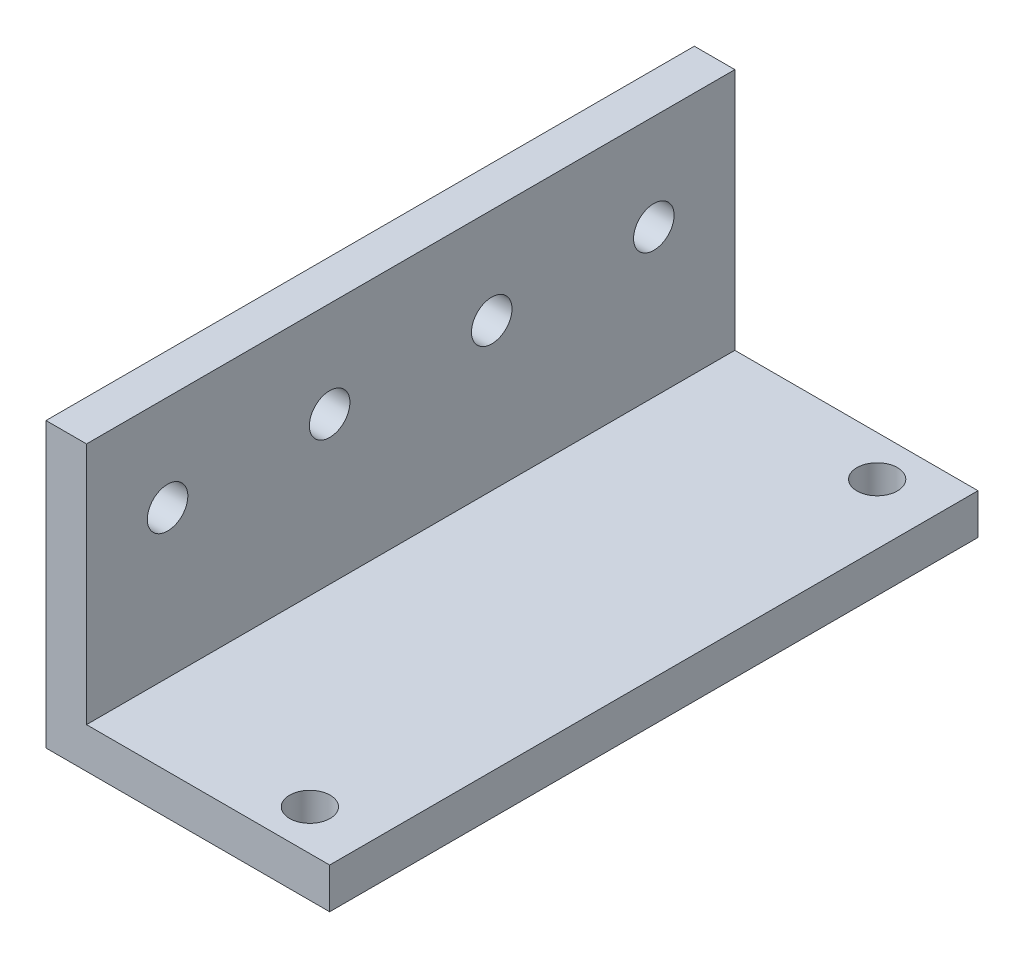
SolidWorks part; units mm, degrees
ref_plane "Front Plane" through (0, 0, 0) normal (0, 0, 1) x (1, 0, 0)
ref_plane "Top Plane" through (0, 0, 0) normal (0, 1, 0) x (1, 0, 0)
ref_plane "Right Plane" through (0, 0, 0) normal (1, 0, 0) x (0, 0, -1)
sketch "Sketch1" plane through (0, 0, 0) normal (0, 0, 1) x (1, 0, 0)
  line L1 (0, 0) -> (44.45, 0)
  line L2 (0, 0) -> (0, 44.45)
  line L3 (0, 44.45) -> (44.45, 44.45)
  line L4 (44.45, 0) -> (44.45, 44.45)
  line L5 (44.45, 44.45) -> (6.35, 44.45)
  line L6 (44.45, 44.45) -> (44.45, 6.35)
  line L7 (44.45, 6.35) -> (6.35, 6.35)
  line L8 (6.35, 44.45) -> (6.35, 6.35)
  dimension "D1" = 6.35
  dimension "D2" = 6.35
  dimension "D3" = 44.45
  dimension "D4" = 44.45
extrude "Boss-Extrude1" add sketch "Sketch1" along normal blind 101.6 contours L8 L3 L2 L1 L4 L7
sketch "Sketch2" plane through (0, 6.35, 0) normal (0, 1, 0) x (1, 0, 0)
  line L2 (0, 0) -> (44.45, 0) construction
  line L3 (0, -101.6) -> (44.45, -101.6) construction
  circle A0 centre (35, -95.25) radius 3.175
  circle A1 centre (35, -6.35) radius 3.175
  circle A3 centre (35, 332.446) radius 3.175 construction
  dimension "D1" = 6.35
  dimension "D3" = 0
  dimension "D4" = 6.35
extrude "Cut-Extrude1" cut sketch "Sketch2" against normal blind 25.146
sketch "Sketch3" plane through (6.35, 0, 0) normal (1, 0, 0) x (0, 0, -1)
  line L0 (-101.6, 44.45) -> (0, 44.45) construction
  line L1 (0, 44.45) -> (0, 6.35) construction
  circle A0 centre (-12.7, 29.45) radius 3.175
  circle A1 centre (-63.5, 29.45) radius 3.175
  circle A2 centre (-88.9, 29.45) radius 3.175
  circle A3 centre (-38.1, 29.45) radius 3.175
  dimension "D1" = 15
  dimension "D2" = 15
  dimension "D3" = 15
  dimension "D4" = 15
  dimension "D5" = 12.7
  dimension "D6" = 88.9
  dimension "D7" = 38.1
  dimension "D8" = 63.5
extrude "Cut-Extrude2" cut sketch "Sketch3" against normal blind 25.146
